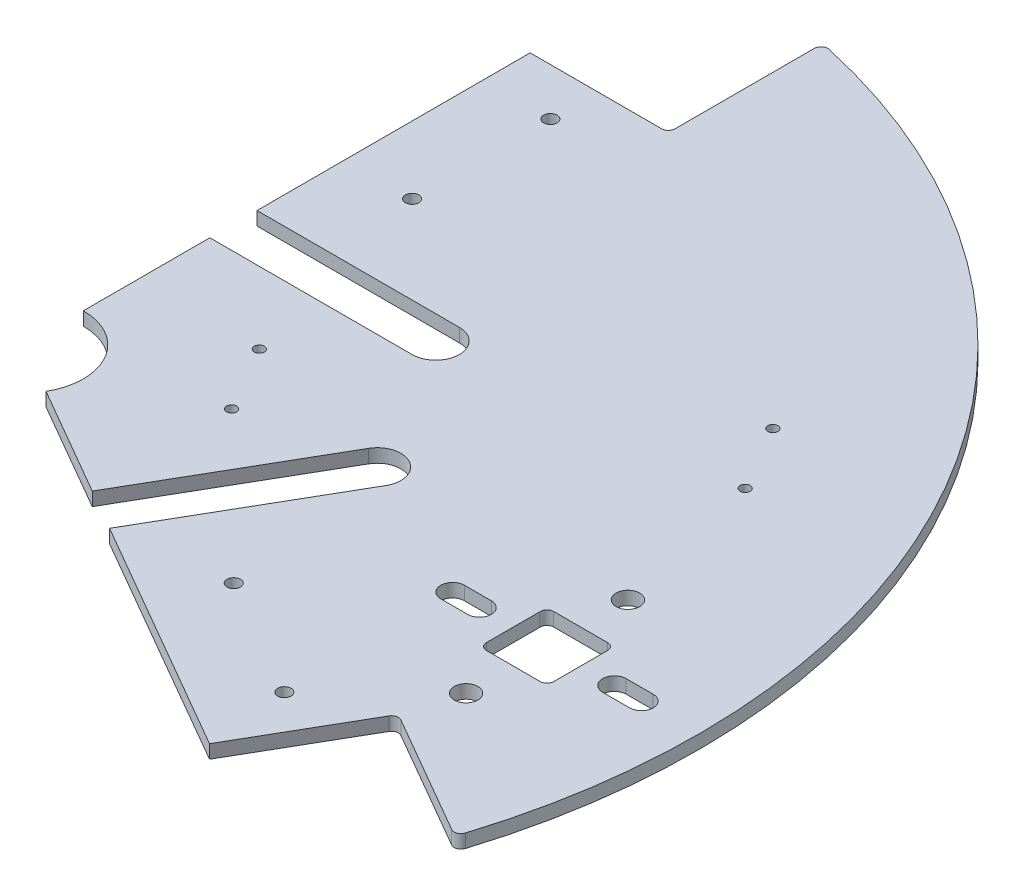
SolidWorks part; units mm, degrees
ref_plane "Front Plane" through (0, 0, 0) normal (0, 0, 1) x (1, 0, 0)
ref_plane "Top Plane" through (0, 0, 0) normal (0, 1, 0) x (1, 0, 0)
ref_plane "Right Plane" through (0, 0, 0) normal (1, 0, 0) x (0, 0, -1)
sketch "Sketch1" plane through (0, 0, 0) normal (0, 1, 0) x (1, 0, 0)
  line L0 (0, 0) -> (0, -150)
  line L1 (0, -150) -> (129.9038, -225)
  line L2 (0, 0) -> (41, 0)
  line L3 (41, 0) -> (41, 45.75)
  line L6 (129.9038, -225) -> (150.4038, -189.493)
  line L7 (150.4038, -189.493) -> (190.0245, -212.368)
  arc A2 (41, 45.75) -> (190.0245, -212.368) centre (-0.003, -150.0018) cw
  dimension "D4" = 41
  dimension "D8" = 200
  dimension "D1" = 150
  dimension "D2" = 150
  dimension "D3" = 120
  dimension "D5" = 45.75
  dimension "D6" = 45.75
  dimension "D7" = 41
extrude "Boss-Extrude1" add sketch "Sketch1" along normal blind 4
sketch "Sketch2" plane through (0, 4, 0) normal (0, 1, 0) x (1, 0, 0)
  line L1 (0, 0) -> (0, -150) construction
  circle A0 centre (20, -14) radius 2
  circle A1 centre (20, -55) radius 2
  dimension "D1" = 4
  dimension "D2" = 4
  dimension "D3" = 41
  dimension "D4" = 95
  dimension "D5" = 20
extrude "Cut-Extrude1" cut sketch "Sketch2" against normal up to surface (4 mm away) up to face at (87.146, 0, 99.6862)
sketch "Sketch3" plane through (0, 4, 0) normal (0, 1, 0) x (1, 0, 0)
  line L0 (0, -150) -> (254.564, -3.0274) construction
  line L1 (0, 0) -> (0, -150) construction
  line L2 (35.9442, -116.2572) -> (47.1942, -135.7428) construction
  circle A0 centre (143.7561, -79.9928) radius 1.5
  circle A1 centre (132.5061, -60.5072) radius 1.5
  circle A2 centre (47.1942, -135.7428) radius 1.5
  circle A3 centre (35.9442, -116.2572) radius 1.5
  dimension "D2" = 3
  dimension "D3" = 3
  dimension "D4" = 3
  dimension "D5" = 3
  dimension "D1" = 60
  dimension "D6" = 22.5
  dimension "D7" = 22.5
  dimension "D8" = 111.5
  dimension "D9" = 48
extrude "Cut-Extrude2" cut sketch "Sketch3" against normal up to surface (4 mm away) up to face at (20, 0, 12)
sketch "Sketch4" plane through (0, 4, 0) normal (0, 1, 0) x (1, 0, 0)
  line L0 (0, 0) -> (0, -150) construction
  line L1 (0, -81) -> (0, -95)
  line L2 (0, -81) -> (60, -81)
  line L3 (60, -95) -> (0, -95)
  arc A0 (60, -81) -> (60, -95) centre (60, -88) cw
  dimension "D1" = 60
  dimension "D2" = 55
  dimension "D3" = 14
extrude "Cut-Extrude3" cut sketch "Sketch4" against normal up to surface (4 mm away) up to face at (143.7561, 0, 78.4928)
sketch "Sketch5" plane through (0, 4, 0) normal (0, 1, 0) x (1, 0, 0)
  line L0 (0, -150) -> (129.9038, -225) construction
  line L1 (92.2724, -180.1795) -> (74.1352, -211.5941) construction
  circle A0 centre (127.7795, -200.6795) radius 2
  circle A1 centre (92.2724, -180.1795) radius 2
  dimension "D1" = 4
  dimension "D2" = 4
  dimension "D3" = 20
  dimension "D4" = 20
  dimension "D5" = 41
  dimension "D6" = 95
extrude "Cut-Extrude4" cut sketch "Sketch5" against normal up to surface (4 mm away) up to face at (67.002, 0, 95.4367)
sketch "Sketch6" plane through (0, 4, 0) normal (0, 1, 0) x (1, 0, 0)
  line L0 (0, -150) -> (303.3919, -150) construction
  line L1 (0, -150) -> (129.9038, -225) construction
  line L2 (145, -140) -> (165, -140)
  line L3 (145, -160) -> (165, -160)
  line L4 (145, -140) -> (145, -160)
  line L5 (165, -140) -> (165, -160)
  line L6 (155, -140) -> (155, -160) construction
  line L7 (127, -150) -> (135, -150) construction
  line L8 (127, -146.5) -> (135, -146.5)
  line L9 (127, -153.5) -> (135, -153.5)
  line L10 (183, -150) -> (175, -150) construction
  line L11 (183, -146.5) -> (175, -146.5)
  line L12 (183, -153.5) -> (175, -153.5)
  arc A0 (127, -146.5) -> (127, -153.5) centre (127, -150) ccw
  arc A1 (135, -153.5) -> (135, -146.5) centre (135, -150) ccw
  circle A2 centre (155, -174) radius 3.5
  arc A3 (183, -146.5) -> (183, -153.5) centre (183, -150) cw
  arc A4 (175, -153.5) -> (175, -146.5) centre (175, -150) cw
  circle A5 centre (155, -126) radius 3.5
  point P13 (131, -150)
  point P22 (179, -150)
  dimension "D8" = 7
  dimension "D1" = 30
  dimension "D2" = 20
  dimension "D3" = 145
  dimension "D4" = 20
  dimension "D5" = 7
  dimension "D6" = 8
  dimension "D7" = 10
  dimension "D9" = 10
  dimension "D10" = 14
extrude "Cut-Extrude5" cut sketch "Sketch6" against normal up to surface (4 mm away) up to face at (127.7795, 0, 198.6795)
sketch "Sketch8" plane through (0, 4, 0) normal (0, 1, 0) x (1, 0, 0)
  line L0 (47.6314, -177.5) -> (59.7558, -184.5)
  line L4 (47.6314, -177.5) -> (77.6314, -125.5385)
  line L5 (0, -150) -> (129.9038, -225) construction
  line L6 (89.7558, -132.5385) -> (59.7558, -184.5)
  arc A1 (77.6314, -125.5385) -> (89.7558, -132.5385) centre (83.6936, -129.0385) cw
  dimension "D1" = 60
  dimension "D2" = 55
  dimension "D3" = 14
extrude "Cut-Extrude6" cut sketch "Sketch8" against normal up to surface (4 mm away) up to face at (131, 0, 150)
sketch "Sketch9" plane through (0, 4, 0) normal (0, 1, 0) x (1, 0, 0)
  circle A0 centre (0, -150) radius 17.5
  dimension "D1" = 35
extrude "Cut-Extrude7" cut sketch "Sketch9" against normal up to surface (4 mm away) up to face at (67.6864, 0, 110.9212)
fillet "Fillet1" radius 2 8 edges at (41, 2, -45.75) (41, 2, 0) (165, 2, 140) (145, 2, 160) (165, 2, 160) (145, 2, 140) (190.0245, 2, 212.368) (150.4038, 2, 189.493)
